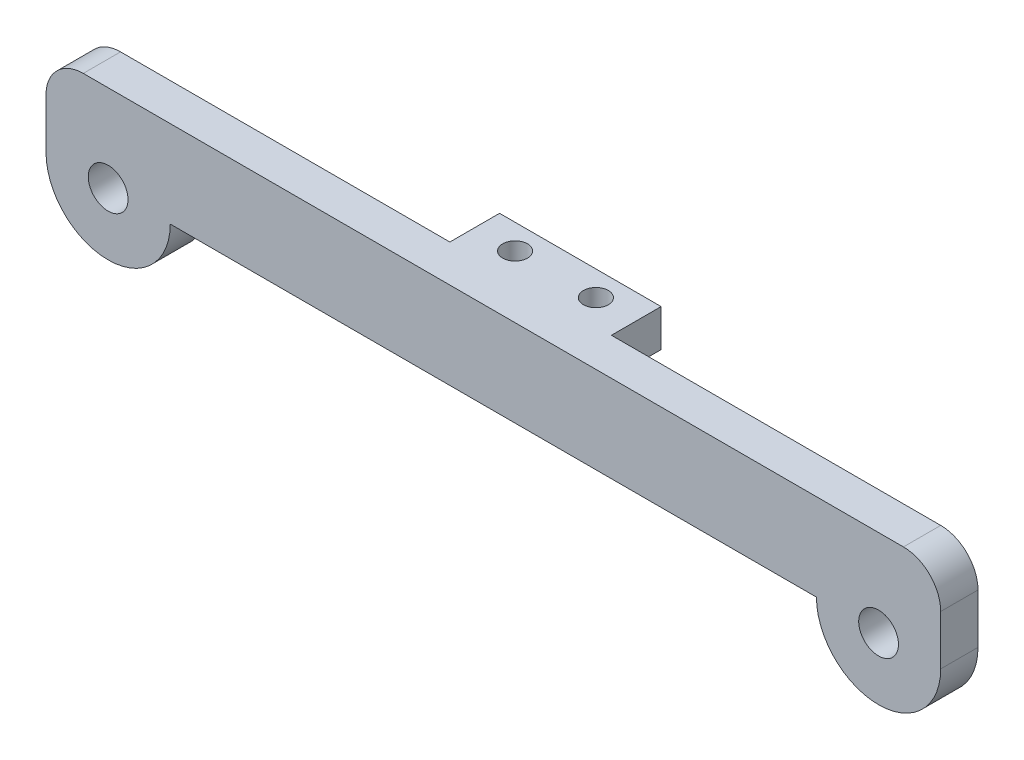
SolidWorks part; units mm, degrees
ref_plane "正面" through (0, 0, 0) normal (0, 0, 1) x (1, 0, 0)
ref_plane "平面" through (0, 0, 0) normal (0, 1, 0) x (1, 0, 0)
ref_plane "右側面" through (0, 0, 0) normal (1, 0, 0) x (0, 0, -1)
sketch "ｽｹｯﾁ1" plane through (0, 0, 0) normal (0, 0, 1) x (1, 0, 0)
  line L0 (-31, 0) -> (31, 0) construction
  line L1 (-31, 5) -> (31, 5) construction
  line L2 (-26, 0) -> (26, 0)
  line L3 (-36, 0) -> (-36, 7)
  line L4 (-36, 7) -> (36, 7)
  line L5 (36, 7) -> (36, 0)
  circle A0 centre (-31, 0) radius 1.6
  circle A1 centre (31, 0) radius 1.6
  arc A2 (-31, 5) -> (-26, 0) centre (-31, 0) ccw construction
  arc A3 (26, 0) -> (31, 5) centre (31, 0) ccw construction
  arc A4 (-36, 0) -> (-26, 0) centre (-31, 0) ccw
  arc A5 (26, 0) -> (36, 0) centre (31, 0) ccw
  point P4 (0, 0)
  dimension "D1" = 3.2
  dimension "D3" = 10
  dimension "D2" = 62
  dimension "D4" = 2
extrude "ﾎﾞｽ - 押し出し1" add sketch "ｽｹｯﾁ1" along normal blind 3
sketch "ｽｹｯﾁ6" plane through (0, 7, 0) normal (0, 1, 0) x (1, 0, 0)
  line L0 (0, 0) -> (0, 2) construction
  line L1 (36, 0) -> (-36, 0) construction
  line L2 (-6.5, 4) -> (6.5, 4)
  line L3 (-6.5, 4) -> (-6.5, 0)
  line L4 (-6.5, 0) -> (6.5, 0)
  line L5 (6.5, 4) -> (6.5, 0)
  line L6 (-6.5, 4) -> (6.5, 0) construction
  line L7 (-6.5, 0) -> (6.5, 4) construction
  line L8 (-3.25, 2) -> (3.25, 2) construction
  line L9 (36, -3) -> (-36, -3) construction
  circle A0 centre (-3.25, 2) radius 1
  circle A1 centre (3.25, 2) radius 1
  point P11 (0, 2)
  dimension "D2" = 6.5
  dimension "D3" = 5
  dimension "D4" = 2
  dimension "D1" = 13
extrude "ﾎﾞｽ - 押し出し3" add sketch "ｽｹｯﾁ6" against normal blind 3
fillet "ﾌｨﾚｯﾄ1" radius 3 2 edges at (-36, 7, 1.5) (36, 7, 1.5)
